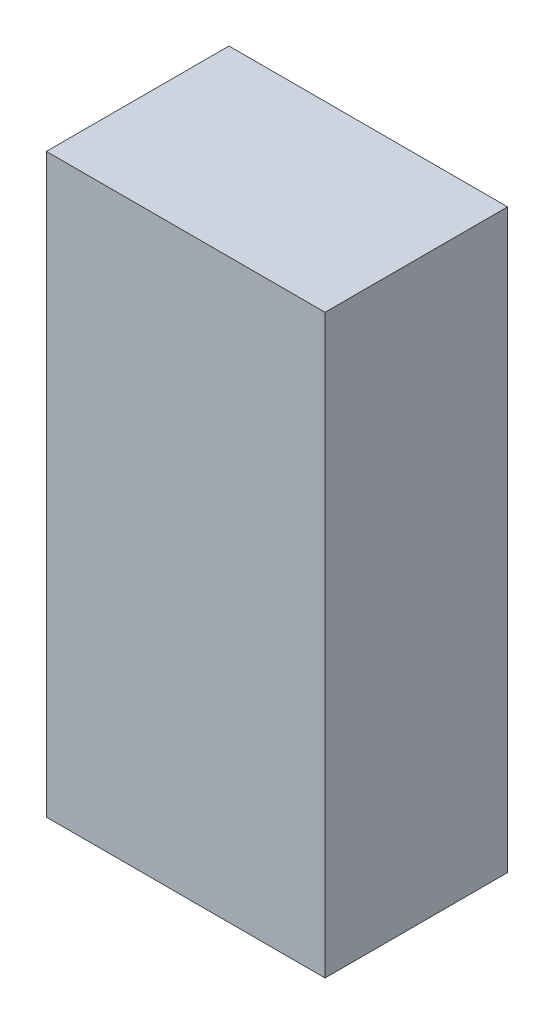
SolidWorks part; units mm, degrees
material "Copper"
ref_plane "Front Plane" through (0, 0, 0) normal (0, 0, 1) x (1, 0, 0)
ref_plane "Top Plane" through (0, 0, 0) normal (0, 1, 0) x (1, 0, 0)
ref_plane "Right Plane" through (0, 0, 0) normal (1, 0, 0) x (0, 0, -1)
sketch "Sketch1" plane through (0, 0, 0) normal (0, 1, 0) x (1, 0, 0)
  line L1 (0, 0) -> (368.3, 0)
  line L2 (0, 0) -> (0, 241.3)
  line L3 (0, 241.3) -> (368.3, 241.3)
  line L4 (368.3, 0) -> (368.3, 241.3)
  dimension "D1" = 368.3
  dimension "D2" = 241.3
extrude "Extrude1" add sketch "Sketch1" along normal blind 762
